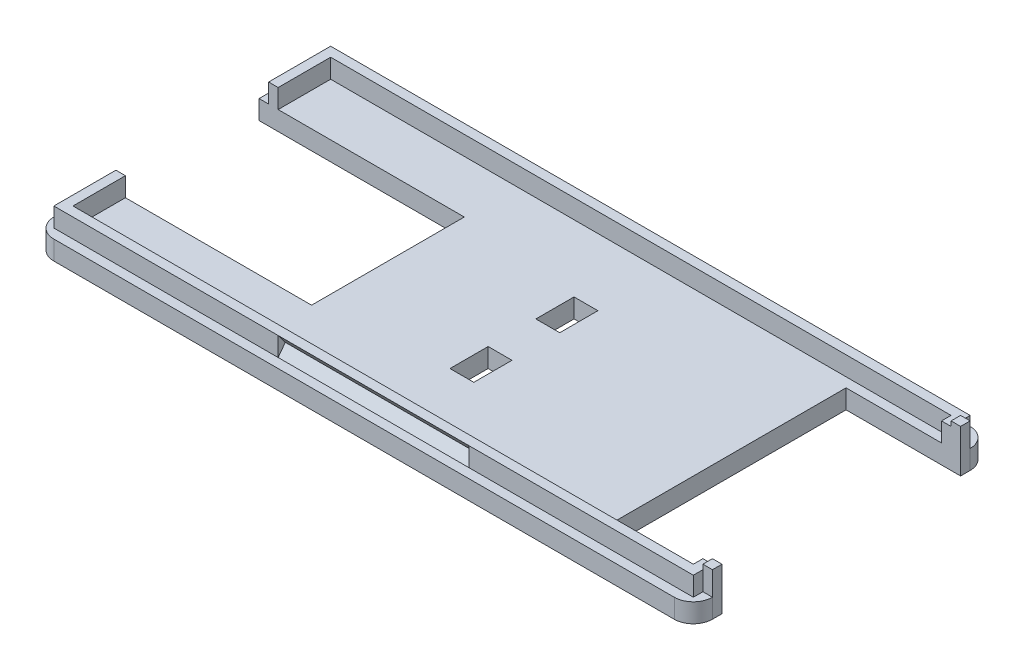
SolidWorks part; units mm, degrees
ref_plane "Front Plane" through (0, 0, 0) normal (0, 0, 1) x (1, 0, 0)
ref_plane "Top Plane" through (0, 0, 0) normal (0, 1, 0) x (1, 0, 0)
ref_plane "Right Plane" through (0, 0, 0) normal (1, 0, 0) x (0, 0, -1)
sketch "Sketch1" plane through (0, 0, 0) normal (0, 1, 0) x (1, 0, 0)
  line L0 (-32.5, -15.5) -> (32.5, -15.5)
  line L1 (-34.5, -13.5) -> (-34.5, 13.5)
  line L2 (-32.5, 15.5) -> (32.5, 15.5)
  line L3 (34.5, -13.5) -> (34.5, 13.5)
  line L4 (-34.5, -15.5) -> (34.5, 15.5) construction
  line L5 (-34.5, 15.5) -> (34.5, -15.5) construction
  arc A0 (-32.5, -15.5) -> (-34.5, -13.5) centre (-32.5, -13.5) cw
  arc A1 (32.5, -15.5) -> (34.5, -13.5) centre (32.5, -13.5) ccw
  arc A2 (32.5, 15.5) -> (34.5, 13.5) centre (32.5, 13.5) cw
  arc A3 (-34.5, 13.5) -> (-32.5, 15.5) centre (-32.5, 13.5) cw
  point P0 (0, 0)
  dimension "D1" = 2
  dimension "D2" = 69
  dimension "D3" = 31
extrude "Boss-Extrude1" add sketch "Sketch1" along normal mid plane 2
sketch "Sketch3" plane through (0, 1, 0) normal (0, 1, 0) x (1, 0, 0)
  line L0 (32.5, 15.5) -> (-32.5, 15.5) construction
  line L1 (-33.5, -14.5) -> (33.5, -14.5)
  line L2 (-33.5, -14.5) -> (-33.5, 14.5)
  line L3 (-33.5, 14.5) -> (33.5, 14.5)
  line L4 (33.5, -14.5) -> (33.5, 14.5)
  line L5 (-33.5, -14.5) -> (33.5, 14.5) construction
  line L6 (-33.5, 14.5) -> (33.5, -14.5) construction
  line L7 (34.5, -13.5) -> (34.5, 13.5) construction
  line L9 (-32.5, -13.5) -> (32.5, -13.5)
  line L10 (-32.5, -13.5) -> (-32.5, 13.5)
  line L11 (-32.5, 13.5) -> (32.5, 13.5)
  line L12 (32.5, -13.5) -> (32.5, 13.5)
  line L13 (-32.5, -13.5) -> (32.5, 13.5) construction
  line L14 (-32.5, 13.5) -> (32.5, -13.5) construction
  point P0 (0, 0)
  point P10 (0, 0)
  dimension "D1" = 1
  dimension "D2" = 1
  dimension "D3" = 1
  dimension "D4" = 1
extrude "Boss-Extrude2" add sketch "Sketch3" along normal blind 2
sketch "Sketch6" plane through (0, 0, 0) normal (1, 0, 0) x (0, 0, -1)
  line L4 (14.5, 1) -> (14.5, 3)
  line L5 (14.5, 3) -> (13.75, 2)
  line L6 (13.75, 2) -> (14.5, 1)
  line L7 (0, 0) -> (0, 9.5118) construction
  line L8 (-13.75, 2) -> (-14.5, 1)
  line L9 (-14.5, 1) -> (-14.5, 3)
  line L10 (-14.5, 3) -> (-13.75, 2)
  point P15 (14.5, 2)
  dimension "D2" = 0.75
  dimension "D3" = 1
extrude "Cut-Extrude1" cut sketch "Sketch6" against normal mid plane 20
sketch "Sketch7" plane through (0, -1, 0) normal (0, -1, 0) x (1, 0, 0)
  line L0 (-34.5, -13.5) -> (-34.5, 13.5) construction
  line L1 (-34.5, 8) -> (-13, 8)
  line L2 (-34.5, 8) -> (-34.5, -8)
  line L3 (-34.5, -8) -> (-13, -8)
  line L4 (-13, 8) -> (-13, -8)
  line L5 (34.5, 13.5) -> (34.5, -13.5) construction
  line L6 (34.5, -12.5) -> (22.5, -12.5)
  line L7 (34.5, -12.5) -> (34.5, 12.5)
  line L8 (34.5, 12.5) -> (22.5, 12.5)
  line L9 (22.5, -12.5) -> (22.5, 12.5)
  point P6 (-34.5, 0)
  point P7 (-34.5, 0)
  point P14 (34.5, 0)
  point P16 (34.5, 0)
  dimension "D1" = 21.5
  dimension "D2" = 16
  dimension "D3" = 12
  dimension "D4" = 25
extrude "Cut-Extrude2" cut sketch "Sketch7" against normal blind 20
sketch "Sketch11" plane through (0, 1, 0) normal (0, 1, 0) x (1, 0, 0)
  line L0 (0, 0) -> (45.3077, 0) construction
  line L1 (33.5, 12.5) -> (34.5, 12.5)
  line L2 (33.5, 12.5) -> (33.5, 13.5)
  line L3 (33.5, 13.5) -> (34.5, 13.5)
  line L4 (34.5, 12.5) -> (34.5, 13.5)
  line L5 (33.5, -13.5) -> (34.5, -13.5)
  line L6 (34.5, -12.5) -> (34.5, -13.5)
  line L7 (33.5, -12.5) -> (34.5, -12.5)
  line L8 (33.5, -12.5) -> (33.5, -13.5)
extrude "Boss-Extrude5" add sketch "Sketch11" along normal blind 2.5
sketch "Sketch12" plane through (0, -1, 0) normal (0, -1, 0) x (1, 0, 0)
  line L0 (18.2915, 15.5) -> (18.2915, -15.5) construction
  line L1 (-32.5, 15.5) -> (32.5, 15.5) construction
  line L2 (32.5, -15.5) -> (-32.5, -15.5) construction
  text T0 "<b>CV  T </b>" font "Century Gothic" height in points 24
extrude "Cut-Extrude3" cut sketch "Sketch12" against normal blind 0.5
sketch "Sketch13" plane through (0, -1, 0) normal (0, -1, 0) x (1, 0, 0)
  line L0 (-34.5, 8) -> (-34.5, 13.5) construction
  line L1 (0, 6.5) -> (2.5, 6.5)
  line L2 (0, 6.5) -> (0, 2.5)
  line L3 (0, 2.5) -> (2.5, 2.5)
  line L4 (2.5, 6.5) -> (2.5, 2.5)
  line L5 (-32.5, 15.5) -> (32.5, 15.5) construction
  line L6 (32.5, -15.5) -> (-32.5, -15.5) construction
  line L7 (0, -2.5) -> (2.5, -2.5)
  line L8 (0, -2.5) -> (0, -6.5)
  line L9 (0, -6.5) -> (2.5, -6.5)
  line L10 (2.5, -2.5) -> (2.5, -6.5)
  line L12 (-34.5, -13.5) -> (-34.5, -8) construction
  dimension "D1" = 34.5
  dimension "D2" = 9
  dimension "D3" = 4
  dimension "D4" = 2.5
  dimension "D5" = 9
  dimension "D6" = 2.5
  dimension "D7" = 4
  dimension "D8" = 34.5
extrude "Cut-Extrude4" cut sketch "Sketch13" against normal through all
